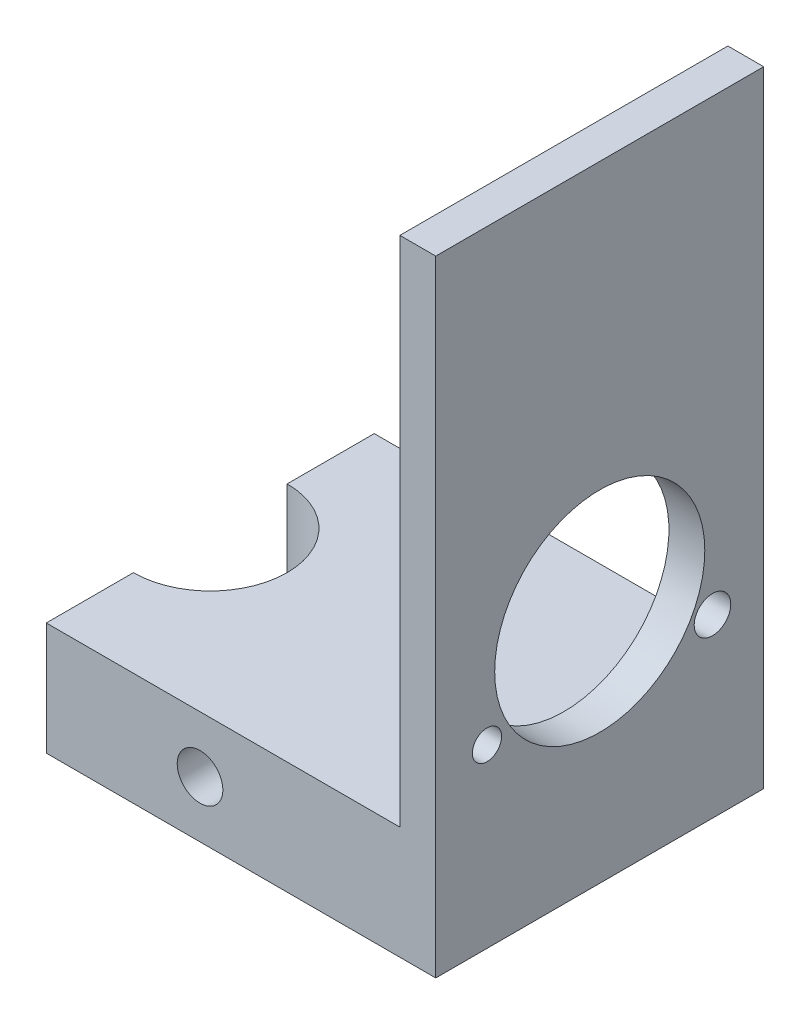
SolidWorks part; units mm, degrees
ref_plane "Front Plane" through (0, 0, 0) normal (0, 0, 1) x (1, 0, 0)
ref_plane "Top Plane" through (0, 0, 0) normal (0, 1, 0) x (1, 0, 0)
ref_plane "Right Plane" through (0, 0, 0) normal (1, 0, 0) x (0, 0, -1)
sketch "Sketch1" plane through (0, 0, 0) normal (0, 1, 0) x (1, 0, 0)
  line L1 (0, 16) -> (38, 16)
  line L2 (0, 16) -> (0, -16)
  line L3 (0, -16) -> (38, -16)
  line L4 (38, 16) -> (38, -16)
  circle A0 centre (0, 0) radius 7.5
  dimension "D1" = 15
  dimension "D2" = 16
  dimension "D3" = 16
  dimension "D4" = 38
extrude "Boss-Extrude1" add sketch "Sketch1" along normal blind 11 contours A0 L2 L3 L4 L1
sketch "Sketch2" plane through (0, 11, 0) normal (0, 1, 0) x (1, 0, 0)
  line L0 (0, -16) -> (38, -16) construction
  line L1 (38, 16) -> (34.5, 16)
  line L2 (38, 16) -> (38, -16)
  line L3 (38, -16) -> (34.5, -16)
  line L4 (34.5, 16) -> (34.5, -16)
  line L5 (0, -7.5) -> (0, -16) construction
  dimension "D1" = 34.5
extrude "Boss-Extrude2" add sketch "Sketch2" along normal blind 50
sketch "Sketch3" plane through (34.5, 0, 0) normal (-1, 0, 0) x (0, 0, 1)
  line L0 (-16, 11) -> (16, 11) construction
  circle A0 centre (0, 23) radius 10.25
  circle A1 centre (-11, 17.2028) radius 1.7836
  circle A2 centre (11, 17.2028) radius 1.4262
  dimension "D1" = 20.5
  dimension "D2" = 12
  dimension "D3" = 11
  dimension "D4" = 11
extrude "Cut-Extrude1" cut sketch "Sketch3" against normal blind 50
sketch "Sketch4" plane through (0, 0, -16) normal (0, 0, -1) x (-1, 0, 0)
  line L0 (0, 11) -> (0, 0) construction
  line L1 (0, 11) -> (-34.5, 11) construction
  circle A0 centre (-15, 5.5) radius 2.2265
  dimension "D1" = 5.5
  dimension "D2" = 15
extrude "Cut-Extrude2" cut sketch "Sketch4" against normal blind 36
